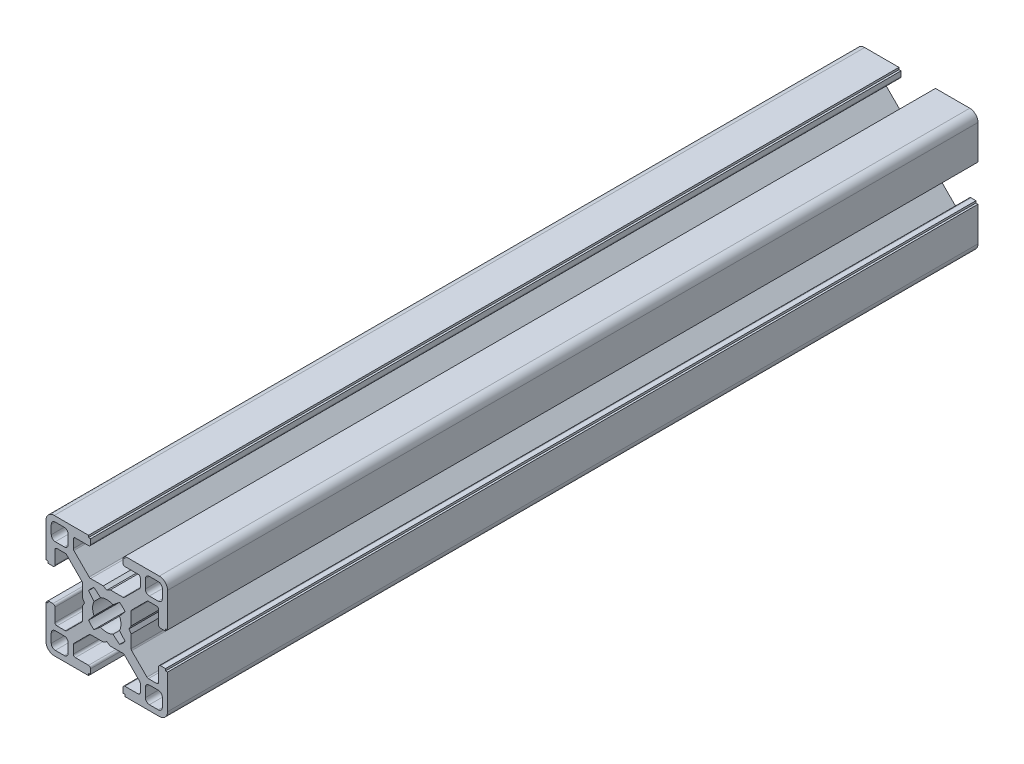
SolidWorks part; units mm, degrees
ref_plane "Front Plane" through (0, 0, 0) normal (0, 0, 1) x (1, 0, 0)
ref_plane "Top Plane" through (0, 0, 0) normal (0, 1, 0) x (1, 0, 0)
ref_plane "Right Plane" through (0, 0, 0) normal (1, 0, 0) x (0, 0, -1)
sketch "Sketch1" plane through (0, 0, 0) normal (0, 0, 1) x (1, 0, 0)
  line L0 (-15, 0) -> (15, 0) construction
  line L1 (0, -15) -> (0, 15) construction
  line L2 (-4.5, 15) -> (4.5, 15) construction
  line L3 (-4, -15) -> (4, -15) construction
  line L4 (-4.5, 15) -> (-4.5, 14.5)
  line L5 (-4.5, 14.5) -> (-4, 14.5)
  line L6 (-4, 14.5) -> (-4, 13.29)
  line L7 (-4.5, 12.79) -> (-7.7675, 12.79)
  line L8 (-8.2675, 12.29) -> (-8.2675, 10.2707)
  line L9 (-8.1211, 9.9171) -> (-4.3504, 6.1464)
  line L10 (-3.9968, 6) -> (0, 6)
  line L11 (0, 0) -> (-15, 15) construction
  line L12 (-4.5, 15) -> (-12.968, 15)
  line L14 (-12.705, 9.5135) -> (-10.5135, 9.5135)
  line L15 (-13.705, 10.5135) -> (-13.705, 12.705)
  line L16 (-12.705, 13.705) -> (-10.5135, 13.705)
  line L17 (-9.5135, 10.5135) -> (-9.5135, 12.705)
  line L18 (-13.705, 9.5135) -> (-9.5135, 13.705) construction
  line L19 (-13.705, 13.705) -> (-9.5135, 9.5135) construction
  line L20 (-3.1568, 4.5038) -> (-1.5303, 3.1477) construction
  line L21 (-4.5038, 3.1568) -> (-3.1477, 1.5303) construction
  line L22 (-6, 3.9968) -> (-6, 0)
  line L23 (-9.9171, 8.1211) -> (-6.1464, 4.3504)
  line L24 (-15, 4.5) -> (-15, 12.968)
  line L25 (-12.29, 8.2675) -> (-10.2707, 8.2675)
  line L26 (-12.79, 4.5) -> (-12.79, 7.7675)
  line L27 (-14.5, 4) -> (-13.29, 4)
  line L28 (-14.5, 4.5) -> (-14.5, 4)
  line L29 (-15, 4.5) -> (-14.5, 4.5)
  circle A0 centre (0, 0) radius 3.5
  arc A1 (-12.968, 15) -> (-15, 12.968) centre (-12.968, 12.968) ccw
  circle A2 centre (0, 0) radius 5.5 construction
  arc A3 (-10.5135, 9.5135) -> (-9.5135, 10.5135) centre (-10.5135, 10.5135) ccw
  arc A4 (-13.705, 12.705) -> (-12.705, 13.705) centre (-12.705, 12.705) cw
  arc A5 (-10.5135, 13.705) -> (-9.5135, 12.705) centre (-10.5135, 12.705) cw
  arc A6 (-12.705, 9.5135) -> (-13.705, 10.5135) centre (-12.705, 10.5135) cw
  arc A7 (-12.79, 4.5) -> (-13.29, 4) centre (-13.29, 4.5) cw
  arc A8 (-12.29, 8.2675) -> (-12.79, 7.7675) centre (-12.29, 7.7675) ccw
  arc A9 (-9.9171, 8.1211) -> (-10.2707, 8.2675) centre (-10.2707, 7.7675) ccw
  arc A10 (-6, 3.9968) -> (-6.1464, 4.3504) centre (-6.5, 3.9968) ccw
  arc A11 (-4.3504, 6.1464) -> (-3.9968, 6) centre (-3.9968, 6.5) ccw
  arc A12 (-4, 13.29) -> (-4.5, 12.79) centre (-4.5, 13.29) cw
  arc A13 (-7.7675, 12.79) -> (-8.2675, 12.29) centre (-7.7675, 12.29) ccw
  arc A14 (-8.2675, 10.2707) -> (-8.1211, 9.9171) centre (-7.7675, 10.2707) ccw
  point P4 (0, 0)
  point P8 (0, 0)
  point P13 (0, 15)
  point P15 (0, -15)
  point P16 (0, 6)
  point P23 (-11.6092, 11.6093)
  point P26 (0, 6)
  point P62 (-12.79, 4)
  point P65 (-12.79, 8.2675)
  point P68 (-10.0636, 8.2675)
  point P71 (-6, 4.2039)
  point P74 (-4.2039, 6)
  point P77 (-4, 12.79)
  point P80 (-8.2675, 12.79)
  point P83 (-8.2675, 10.0636)
  dimension "Center Hole Diameter" = 7
  dimension "D11" = 2.032
  dimension "D9" = 11
  dimension "D13" = 1
  dimension "D14" = 0.5
  dimension "Rail Height" = 30
  dimension "Rail Width" = 30
  dimension "T-Slot Width" = 8
  dimension "T-Slot Depth" = 9
  dimension "D1" = 9
  dimension "D2" = 45
  dimension "D3" = 8
  dimension "D4" = 2.21
  dimension "D5" = 16.535
  dimension "D7" = 2.54
  dimension "D6" = 1.295
  dimension "D8" = 1.246
  dimension "D10" = 10.36
  dimension "D12" = 1.905
sketch "Sketch2" plane through (0, 0, 0) normal (1, 0, 0) x (0, 0, -1)
  line L0 (-76.2, 0) -> (76.2, 0) construction
  line L2 (0, -15) -> (0, 15) construction
  line L3 (0, -15) -> (0, 15) construction
  line L4 (-76.2, -15) -> (-76.2, 15) construction
  line L5 (76.2, -15) -> (76.2, 15) construction
  point P0 (-38.7, 0)
  point P3 (0, 0)
  point P4 (38.7, 0)
  point P12 (-76.2, 0)
  point P14 (76.2, 0)
  dimension "Length" = 152.4
  dimension "D1" = 37.5
sketch "Sketch3" plane through (0, 0, 0) normal (0, 0, 1) x (1, 0, 0)
  line L0 (-4.5038, 3.1568) -> (-3.1477, 1.5303)
  line L1 (0, 3.5) -> (0, 5.5)
  line L2 (-5.5, 0) -> (-3.5, 0)
  line L7 (-6, 3.9968) -> (-6, 0) construction
  line L31 (-9.9171, 8.1211) -> (-6.1464, 4.3504) construction
  line L117 (-12.29, 8.2675) -> (-10.2707, 8.2675) construction
  line L118 (-12.79, 4.5) -> (-12.79, 7.7675) construction
  line L157 (-12.705, 9.5135) -> (-10.5135, 9.5135)
  line L158 (-9.5135, 10.5135) -> (-9.5135, 12.705)
  line L163 (-10.5135, 13.705) -> (-12.705, 13.705)
  line L164 (-13.705, 12.705) -> (-13.705, 10.5135)
  line L165 (-12.705, 9.5135) -> (-10.5135, 9.5135)
  line L166 (-9.5135, 10.5135) -> (-9.5135, 12.705)
  line L167 (-10.5135, 13.705) -> (-12.705, 13.705)
  line L168 (-13.705, 12.705) -> (-13.705, 10.5135)
  line L169 (-14.5, 4) -> (-13.29, 4) construction
  line L170 (-14.5, 4.5) -> (-14.5, 4) construction
  line L171 (-15, 4.5) -> (-14.5, 4.5) construction
  line L172 (-15, 4.5) -> (-15, 12.968) construction
  line L173 (-4.5, 15) -> (-12.968, 15) construction
  line L174 (-4.5, 15) -> (-4.5, 14.5) construction
  line L175 (-4.5, 14.5) -> (-4, 14.5) construction
  line L176 (-4, 14.5) -> (-4, 13.29) construction
  line L177 (-4.5, 12.79) -> (-7.7675, 12.79) construction
  line L178 (-8.2675, 12.29) -> (-8.2675, 10.2707) construction
  line L179 (-8.1211, 9.9171) -> (-4.3504, 6.1464) construction
  line L180 (-3.9968, 6) -> (0, 6) construction
  line L181 (-6, 3.9968) -> (-6, 0.866)
  line L182 (-9.9171, 8.1211) -> (-6.1464, 4.3504)
  line L183 (-12.29, 8.2675) -> (-10.2707, 8.2675)
  line L184 (-12.79, 4.5) -> (-12.79, 7.7675)
  line L185 (-14.5, 4) -> (-13.29, 4)
  line L186 (-14.5, 4.5) -> (-14.5, 4)
  line L187 (-15, 4.5) -> (-14.5, 4.5)
  line L188 (-15, 4.5) -> (-15, 12.968)
  line L189 (-4.5, 15) -> (-12.968, 15)
  line L190 (-4.5, 15) -> (-4.5, 14.5)
  line L191 (-4.5, 14.5) -> (-4, 14.5)
  line L192 (-4, 14.5) -> (-4, 13.29)
  line L193 (-4.5, 12.79) -> (-7.7675, 12.79)
  line L194 (-8.2675, 12.29) -> (-8.2675, 10.2707)
  line L195 (-8.1211, 9.9171) -> (-4.3504, 6.1464)
  line L196 (-3.9968, 6) -> (-0.866, 6)
  line L197 (-0.866, 6) -> (0, 5.5)
  line L198 (0, -15) -> (0, 15) construction
  line L199 (0, 0) -> (-15, 15) construction
  line L200 (0, 0) -> (-15, 15) construction
  line L201 (-3.1568, 4.5038) -> (-1.5303, 3.1477) construction
  line L202 (-3.1568, 4.5038) -> (-1.5303, 3.1477)
  line L203 (-6, 0.866) -> (-5.5, 0)
  line L204 (-15, 0) -> (15, 0) construction
  line L205 (-15, 0) -> (15, 0) construction
  line L206 (0, -15) -> (0, 15) construction
  arc A0 (-3.5, 0) -> (-3.1477, 1.5303) centre (0, 0) cw
  arc A10 (-6, 3.9968) -> (-6.1464, 4.3504) centre (-6.5, 3.9968) ccw construction
  circle A16 centre (0, 0) radius 3.5
  arc A18 (0, 3.5) -> (-1.5303, 3.1477) centre (0, 0) ccw
  arc A20 (-9.9171, 8.1211) -> (-10.2707, 8.2675) centre (-10.2707, 7.7675) ccw construction
  arc A22 (-12.29, 8.2675) -> (-12.79, 7.7675) centre (-12.29, 7.7675) ccw construction
  arc A28 (-13.29, 4) -> (-12.79, 4.5) centre (-13.29, 4.5) ccw construction
  arc A29 (-10.5135, 9.5135) -> (-9.5135, 10.5135) centre (-10.5135, 10.5135) ccw
  arc A30 (-9.5135, 12.705) -> (-10.5135, 13.705) centre (-10.5135, 12.705) ccw
  arc A31 (-12.705, 13.705) -> (-13.705, 12.705) centre (-12.705, 12.705) ccw
  arc A32 (-13.705, 10.5135) -> (-12.705, 9.5135) centre (-12.705, 10.5135) ccw
  arc A33 (-10.5135, 9.5135) -> (-9.5135, 10.5135) centre (-10.5135, 10.5135) ccw
  arc A34 (-9.5135, 12.705) -> (-10.5135, 13.705) centre (-10.5135, 12.705) ccw
  arc A35 (-12.705, 13.705) -> (-13.705, 12.705) centre (-12.705, 12.705) ccw
  arc A36 (-13.705, 10.5135) -> (-12.705, 9.5135) centre (-12.705, 10.5135) ccw
  arc A37 (-12.968, 15) -> (-15, 12.968) centre (-12.968, 12.968) ccw construction
  arc A38 (-4.5, 12.79) -> (-4, 13.29) centre (-4.5, 13.29) ccw construction
  arc A39 (-7.7675, 12.79) -> (-8.2675, 12.29) centre (-7.7675, 12.29) ccw construction
  arc A40 (-8.2675, 10.2707) -> (-8.1211, 9.9171) centre (-7.7675, 10.2707) ccw construction
  arc A41 (-4.3504, 6.1464) -> (-3.9968, 6) centre (-3.9968, 6.5) ccw construction
  arc A42 (-6, 3.9968) -> (-6.1464, 4.3504) centre (-6.5, 3.9968) ccw
  arc A43 (-9.9171, 8.1211) -> (-10.2707, 8.2675) centre (-10.2707, 7.7675) ccw
  arc A44 (-12.29, 8.2675) -> (-12.79, 7.7675) centre (-12.29, 7.7675) ccw
  arc A45 (-13.29, 4) -> (-12.79, 4.5) centre (-13.29, 4.5) ccw
  arc A46 (-12.968, 15) -> (-15, 12.968) centre (-12.968, 12.968) ccw
  arc A47 (-4.5, 12.79) -> (-4, 13.29) centre (-4.5, 13.29) ccw
  arc A48 (-7.7675, 12.79) -> (-8.2675, 12.29) centre (-7.7675, 12.29) ccw
  arc A49 (-8.2675, 10.2707) -> (-8.1211, 9.9171) centre (-7.7675, 10.2707) ccw
  arc A50 (-4.3504, 6.1464) -> (-3.9968, 6) centre (-3.9968, 6.5) ccw
  circle A51 centre (0, 0) radius 5.5 construction
  arc A52 (-3.1568, 4.5038) -> (-4.5038, 3.1568) centre (0, 0) ccw
  dimension "D3" = 60
  dimension "D4" = 60
  dimension "D1" = 0
  dimension "D2" = 0
extrude "Boss-Extrude1" add sketch "Sketch3" along normal mid plane 200
pattern_circular "CirPattern1" count 4 over 360 about axis through (0, 0, 0) along (0, 0, 1) of "Boss-Extrude1"
ref_plane "Contact Plane1" through (15, 0, 0) normal (1, 0, 0) x (0, 0, -1)
ref_plane "Contact Plane2" through (0, -15, 0) normal (0, 1, 0) x (1, 0, 0)
ref_plane "Contact Plane3" through (-15, 0, 0) normal (1, 0, 0) x (0, 0, -1)
ref_plane "Contact Plane4" through (0, 15, 0) normal (0, 1, 0) x (1, 0, 0)
equation "\"D1@Sketch2\" = \"Rail Height@Sketch1\" * 1.25"
equation "\"D1@Sketch1\"=\"T-Slot Width@Sketch1\"+1mm"
equation "\"D3@Sketch1\"=\"T-Slot Width@Sketch1\""
equation "\"D1@Boss-Extrude1\"=\"Width\""
equation "\"Width\"= 200mm"
